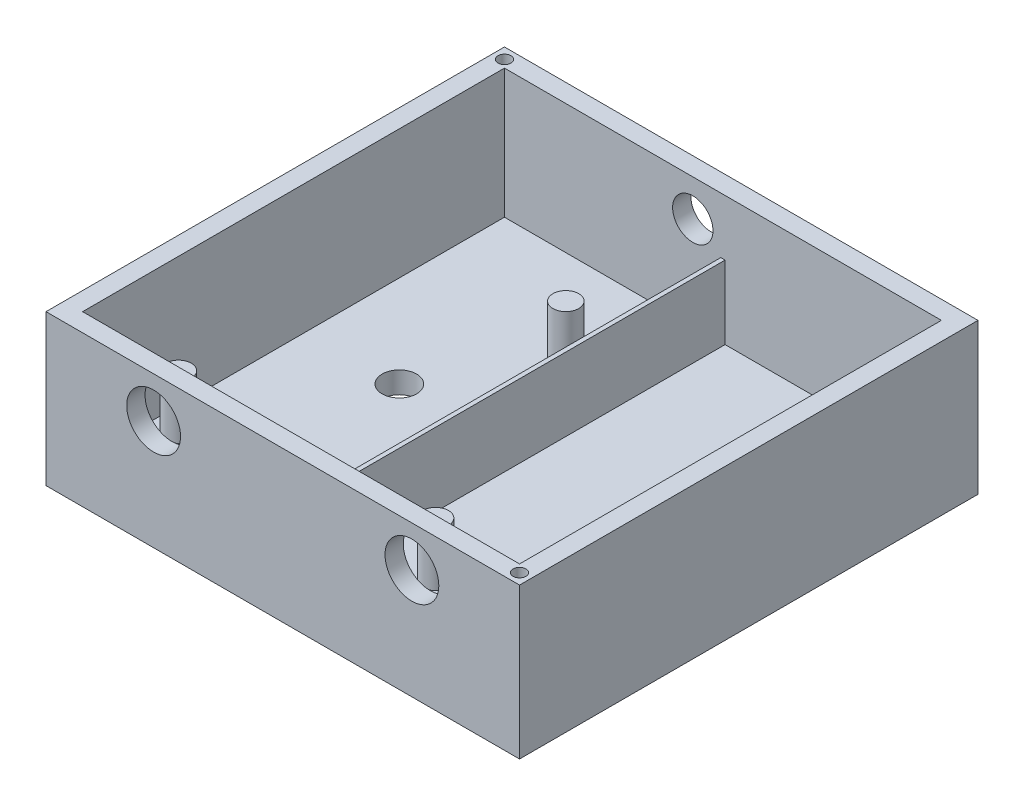
SolidWorks part; units mm, degrees
other "Markup1"
sketch "Sketch12" plane through (0, 17.78, -54.102) normal (0, 1, 0) x (1, 0, 0)
ref_plane "Front Plane" through (0, 0, 0) normal (0, 0, 1) x (1, 0, 0)
ref_plane "Top Plane" through (0, 0, 0) normal (0, 1, 0) x (1, 0, 0)
ref_plane "Right Plane" through (0, 0, 0) normal (1, 0, 0) x (0, 0, -1)
sketch "Sketch1" plane through (0, 0, 0) normal (0, 1, 0) x (1, 0, 0)
  line L1 (0, 0) -> (55.88, 0)
  line L2 (0, 0) -> (0, 54.102)
  line L3 (0, 54.102) -> (55.88, 54.102)
  line L4 (55.88, 0) -> (55.88, 54.102)
  dimension "D1" = 54.102
  dimension "D2" = 55.88
extrude "Boss-Extrude1" add sketch "Sketch1" along normal blind 17.78
sketch "Sketch3" plane through (0, 17.78, 0) normal (0, 1, 0) x (1, 0, 0)
  line L1 (2.159, 51.943) -> (53.721, 51.943)
  line L2 (2.159, 51.943) -> (2.159, 2.159)
  line L3 (2.159, 2.159) -> (53.721, 2.159)
  line L4 (53.721, 51.943) -> (53.721, 2.159)
  line L12 (0, 54.102) -> (0, 0) construction
  dimension "D1" = 49.784
  dimension "D2" = 51.562
  dimension "D3" = 2.159
extrude "Cut-Extrude1" cut sketch "Sketch3" against normal blind 15.24
sketch "Sketch4" plane through (0, 2.54, 0) normal (0, 1, 0) x (1, 0, 0)
  line L0 (53.721, 2.159) -> (53.721, 51.943) construction
  line L2 (2.159, 51.943) -> (2.159, 2.159) construction
  line L3 (2.159, 51.943) -> (2.159, 2.159) construction
  line L4 (2.159, 2.159) -> (53.721, 2.159) construction
  line L6 (53.721, 2.159) -> (53.721, 51.943) construction
  circle A0 centre (20.701, 40.64) radius 1.524
  circle A1 centre (4.953, 10.668) radius 1.524
  circle A2 centre (50.927, 40.767) radius 1.524
  circle A3 centre (35.179, 10.795) radius 1.524
  dimension "D1" = 3.048
  dimension "D2" = 3.048
  dimension "D3" = 3.048
  dimension "D4" = 3.048
  dimension "D5" = 2.794
  dimension "D6" = 18.542
  dimension "D7" = 8.509
  dimension "D8" = 29.972
  dimension "D9" = 8.636
  dimension "D10" = 2.794
  dimension "D11" = 18.542
  dimension "D12" = 29.972
extrude "Boss-Extrude2" add sketch "Sketch4" along normal blind 6.35
sketch "Sketch6" plane through (0, 2.54, 0) normal (0, 1, 0) x (1, 0, 0)
  line L0 (2.159, 2.159) -> (53.721, 2.159) construction
  line L1 (27.686, 51.943) -> (28.194, 51.943)
  line L2 (27.686, 51.943) -> (27.686, 2.159)
  line L3 (27.686, 2.159) -> (28.194, 2.159)
  line L4 (28.194, 51.943) -> (28.194, 2.159)
  line L5 (27.686, 51.943) -> (28.194, 2.159) construction
  line L6 (27.686, 2.159) -> (28.194, 51.943) construction
  line L7 (2.159, 51.943) -> (2.159, 2.159) construction
  point P0 (27.94, 27.051)
  dimension "D1" = 0.508
  dimension "D2" = 25.527
  dimension "D3" = 49.784
extrude "Boss-Extrude3" add sketch "Sketch6" along normal blind 8.636
sketch "Sketch7" plane through (0, 0, 0) normal (0, 0, 1) x (1, 0, 0)
  line L0 (0, 17.78) -> (0, 0) construction
  line L1 (55.88, 17.78) -> (55.88, 0) construction
  line L2 (0, 17.78) -> (55.88, 17.78) construction
  circle A0 centre (12.7, 12.954) radius 3.175
  circle A1 centre (43.18, 12.954) radius 3.175
  dimension "D1" = 12.7
  dimension "D2" = 12.7
  dimension "D3" = 4.826
  dimension "D4" = 4.826
  dimension "D5" = 6.35
  dimension "D6" = 6.35
extrude "Cut-Extrude3" cut sketch "Sketch7" against normal blind 2.54
sketch "Sketch8" plane through (0, 0, -54.102) normal (0, 0, -1) x (-1, 0, 0)
  line L0 (-55.88, 17.78) -> (0, 17.78) construction
  line L1 (0, 17.78) -> (0, 0) construction
  circle A1 centre (-24.384, 13.462) radius 2.3813
  dimension "D1" = 4.7625
  dimension "D2" = 4.318
  dimension "D3" = 24.384
extrude "Cut-Extrude5" cut sketch "Sketch8" against normal blind 2.54
sketch "Sketch9" plane through (0, 2.54, 0) normal (0, 1, 0) x (1, 0, 0)
  line L0 (27.686, 51.943) -> (2.159, 51.943) construction
  line L1 (2.159, 51.943) -> (2.159, 2.159) construction
  circle A0 centre (12.9966, 28.702) radius 2.032
  dimension "D1" = 4.064
  dimension "D2" = 23.241
  dimension "D3" = 10.8376
extrude "Cut-Extrude6" cut sketch "Sketch9" against normal blind 2.54
sketch "Sketch10" plane through (0, 2.54, 0) normal (0, 1, 0) x (1, 0, 0)
  line L0 (53.721, 51.943) -> (28.194, 51.943) construction
  line L1 (53.721, 2.159) -> (53.721, 51.943) construction
  circle A0 centre (42.5876, 28.702) radius 2.032
  dimension "D1" = 4.064
  dimension "D2" = 23.241
  dimension "D3" = 11.1334
extrude "Cut-Extrude7" cut sketch "Sketch10" against normal blind 2.54
sketch "Sketch11" plane through (0, 17.78, 0) normal (0, 1, 0) x (1, 0, 0)
  line L0 (55.88, 54.102) -> (0, 54.102) construction
  line L1 (0, 54.102) -> (0, 0) construction
  line L2 (55.88, 0) -> (55.88, 54.102) construction
  line L3 (0, 0) -> (55.88, 0) construction
  circle A0 centre (1.27, 52.832) radius 0.762
  circle A1 centre (54.61, 1.27) radius 0.762
  dimension "D1" = 1.524
  dimension "D2" = 1.524
  dimension "D3" = 1.27
  dimension "D4" = 1.27
  dimension "D5" = 1.27
  dimension "D6" = 1.27
extrude "Cut-Extrude8" cut sketch "Sketch11" against normal blind 49.276
